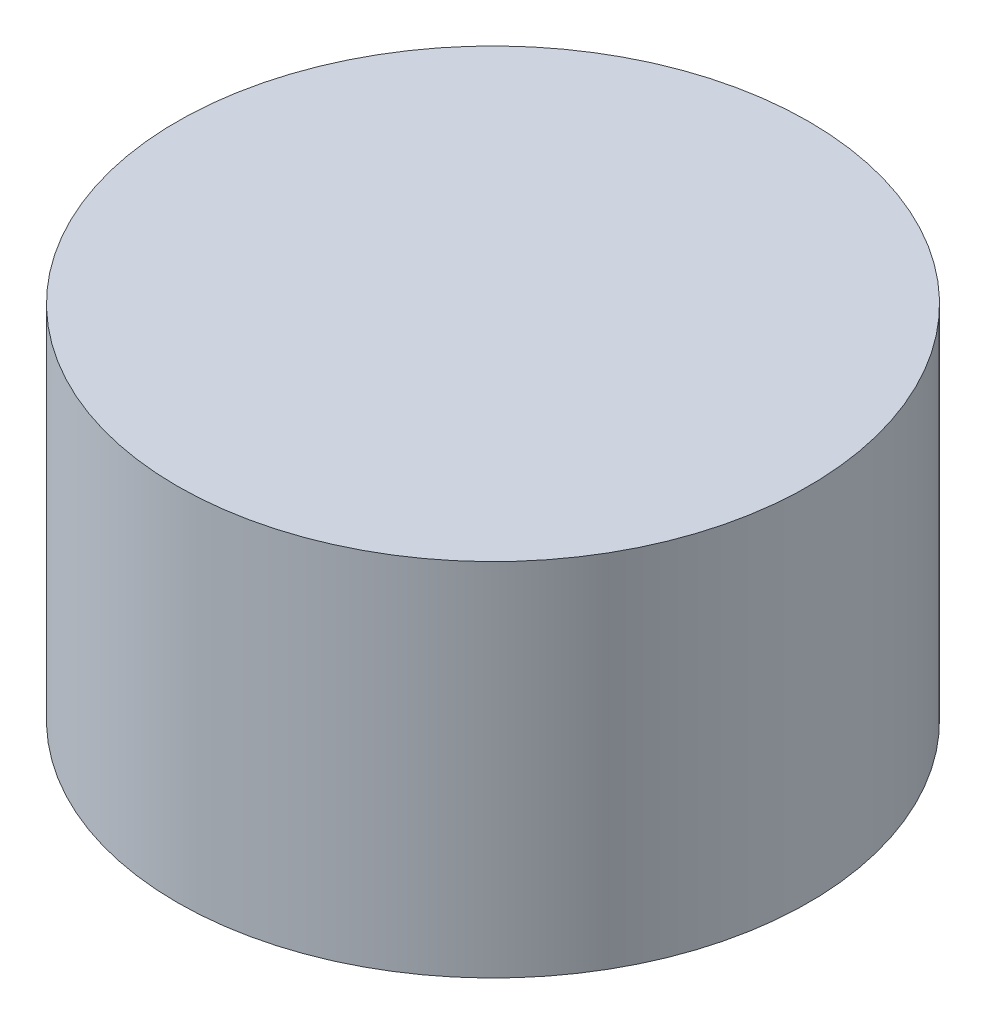
SolidWorks part; units mm, degrees
ref_plane "Front" through (0, 0, 0) normal (0, 0, 1) x (1, 0, 0)
ref_plane "Top" through (0, 0, 0) normal (0, 1, 0) x (1, 0, 0)
ref_plane "Right" through (0, 0, 0) normal (1, 0, 0) x (0, 0, -1)
sketch "Sketch1" plane through (0, 0, 0) normal (0, 1, 0) x (1, 0, 0)
  circle A0 centre (0, 0) radius 37.6511
extrude "Extrude1" add sketch "Sketch1" along normal blind 43
